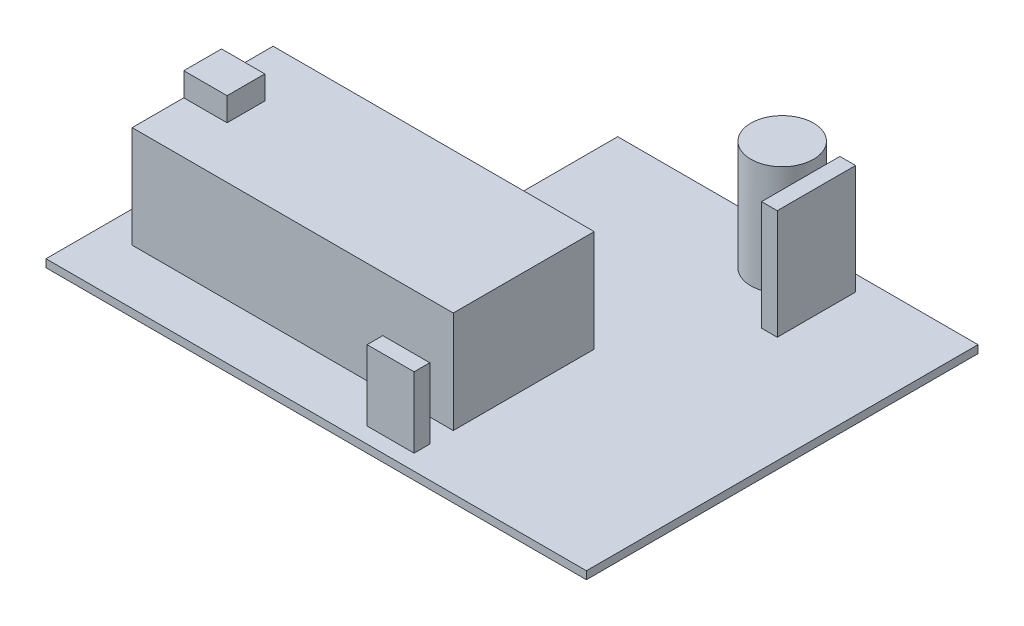
SolidWorks part; units mm, degrees
ref_plane "Front Plane" through (0, 0, 0) normal (0, 0, 1) x (1, 0, 0)
ref_plane "Top Plane" through (0, 0, 0) normal (0, 1, 0) x (1, 0, 0)
ref_plane "Right Plane" through (0, 0, 0) normal (1, 0, 0) x (0, 0, -1)
sketch "Sketch2" plane through (0, 0, 0) normal (0, 1, 0) x (1, 0, 0)
  line L1 (0, 0) -> (69, 0)
  line L2 (0, 0) -> (0, 50)
  line L3 (0, 50) -> (69, 50)
  line L4 (69, 0) -> (69, 50)
  line L5 (0, 50) -> (23, 50)
  line L6 (0, 50) -> (0, 32)
  line L7 (0, 32) -> (23, 32)
  line L8 (23, 50) -> (23, 32)
  dimension "D1" = 69
  dimension "D2" = 50
  dimension "D3" = 23
  dimension "D4" = 18
extrude "Boss-Extrude1" add sketch "Sketch2" along normal blind 1 contours L3 L8 L7 L2 L1 L4
sketch "Sketch3" plane through (0, 1, 0) normal (0, 1, 0) x (1, 0, 0)
  line L0 (0, 0) -> (69, 0) construction
  line L1 (4, 25) -> (45, 25)
  line L2 (4, 25) -> (4, 7)
  line L3 (4, 7) -> (45, 7)
  line L4 (45, 25) -> (45, 7)
  line L5 (0, 0) -> (0, 32) construction
  dimension "D1" = 41
  dimension "D2" = 18
  dimension "D3" = 7
  dimension "D4" = 4
extrude "Boss-Extrude2" add sketch "Sketch3" along normal blind 13
sketch "Sketch4" plane through (0, 14, 0) normal (0, 1, 0) x (1, 0, 0)
  line L0 (4, 25) -> (4, 7) construction
  line L1 (4, 18.4086) -> (9.528, 18.4086)
  line L2 (4, 18.4086) -> (4, 13.5914)
  line L3 (4, 13.5914) -> (9.528, 13.5914)
  line L4 (9.528, 18.4086) -> (9.528, 13.5914)
  line L5 (45, 7) -> (45, 25) construction
  point P6 (9.528, 16)
  point P7 (45, 16)
extrude "Boss-Extrude3" add sketch "Sketch4" along normal blind 3
sketch "Sketch5" plane through (0, 1, 0) normal (0, 1, 0) x (1, 0, 0)
  line L0 (45, 7) -> (45, 25) construction
  line L1 (45, 4) -> (39, 4)
  line L2 (45, 4) -> (45, 2)
  line L3 (45, 2) -> (39, 2)
  line L4 (39, 4) -> (39, 2)
  line L5 (0, 0) -> (69, 0) construction
  dimension "D1" = 6
  dimension "D2" = 2
  dimension "D3" = 2
extrude "Boss-Extrude4" add sketch "Sketch5" along normal blind 9
sketch "Sketch6" plane through (0, 1, 0) normal (0, 1, 0) x (1, 0, 0)
  line L0 (69, 0) -> (69, 50) construction
  line L1 (23, 50) -> (69, 50) construction
  circle A0 centre (48, 46) radius 4
  dimension "D1" = 8
  dimension "D2" = 21
extrude "Boss-Extrude5" add sketch "Sketch6" along normal blind 14
sketch "Sketch7" plane through (0, 1, 0) normal (0, 1, 0) x (1, 0, 0)
  line L0 (48, 50) -> (69, 50) construction
  line L1 (53.3685, 48) -> (55.3685, 48)
  line L2 (53.3685, 48) -> (53.3685, 38)
  line L3 (53.3685, 38) -> (55.3685, 38)
  line L4 (55.3685, 48) -> (55.3685, 38)
  dimension "D1" = 2
  dimension "D2" = 10
  dimension "D3" = 2
extrude "Boss-Extrude6" add sketch "Sketch7" along normal blind 14
